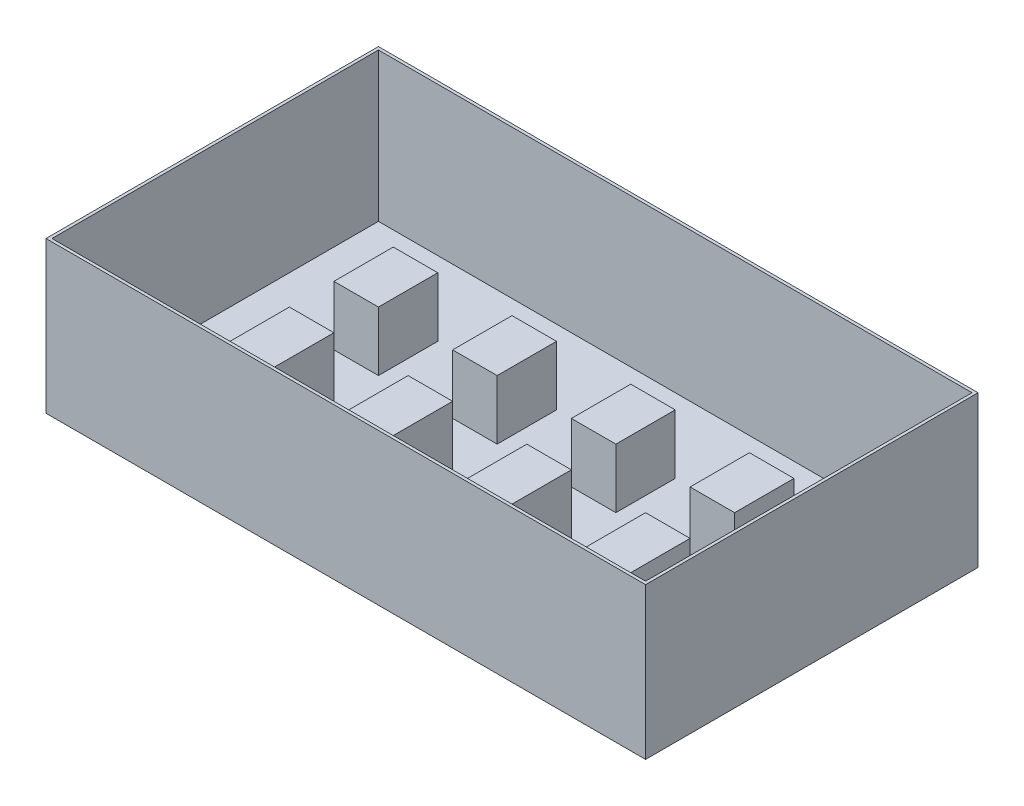
SolidWorks part; units mm, degrees
ref_plane "Front Plane" through (0, 0, 0) normal (0, 0, 1) x (1, 0, 0)
ref_plane "Top Plane" through (0, 0, 0) normal (0, 1, 0) x (1, 0, 0)
ref_plane "Right Plane" through (0, 0, 0) normal (1, 0, 0) x (0, 0, -1)
sketch "Sketch1" plane through (0, 0, 0) normal (0, 1, 0) x (1, 0, 0)
  line L1 (0, 0) -> (2000, 0)
  line L2 (0, 0) -> (0, 1100)
  line L3 (0, 1100) -> (2000, 1100)
  line L4 (2000, 0) -> (2000, 1100)
  dimension "D1" = 2000
  dimension "D2" = 1100
extrude "Boss-Extrude1" add sketch "Sketch1" along normal blind 500
shell "Shell1" thickness 10
sketch "Sketch2" plane through (0, 0, 0) normal (0, 1, 0) x (1, 0, 0)
  line L0 (0, 1100) -> (0, 0) construction
  line L1 (300, 300) -> (450, 300)
  line L2 (300, 300) -> (300, 500)
  line L3 (300, 500) -> (450, 500)
  line L4 (450, 300) -> (450, 500)
  line L5 (0, 0) -> (2000, 0) construction
  dimension "D1" = 300
  dimension "D2" = 300
  dimension "D3" = 200
  dimension "D4" = 150
extrude "Boss-Extrude2" add sketch "Sketch2" along normal blind 200
pattern_linear "LPattern1" count 4 spacing 400 along (1, 0, 0) count 2 spacing 350 along (0, 0, -1) of "Boss-Extrude2"
